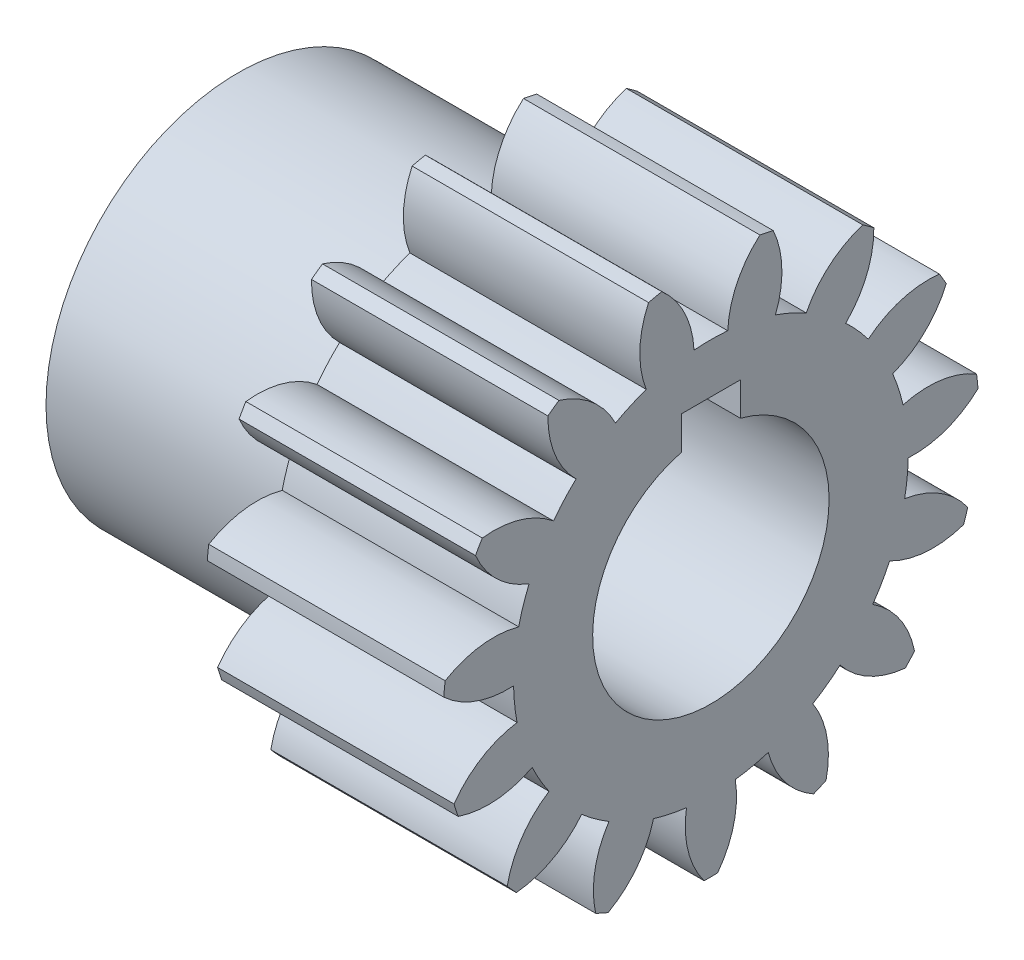
SolidWorks part; units mm, degrees
ref_plane "Plane1" through (0, 0, 0) normal (0, 0, 1) x (1, 0, 0)
ref_plane "Plane2" through (0, 0, 0) normal (0, 1, 0) x (1, 0, 0)
ref_plane "Plane3" through (0, 0, 0) normal (1, 0, 0) x (0, 0, -1)
sketch "HoldingSke" plane through (0, 0, 0) normal (0, 1, 0) x (1, 0, 0)
  line L0 (0, 0) -> (490.6903, -131.4801)
  line L1 (-15, 0) -> (100, 0) construction
  line L2 (0, 0) -> (-2.1039, 2.3779)
  line L3 (0, 0) -> (-11.863, 4.5341)
  line L4 (0, 0) -> (8.3417, 2.2352)
  line L5 (0, 0) -> (-17.849, -6.6571)
  line L6 (0, 0) -> (-7.8959, -5.3274)
  line L7 (-2.1039, 2.3779) -> (1.9966, 20.9814)
  line L8 (-76.2, 54.61) -> (-65.4837, 54.61)
  line L9 (-71.009, 38.7566) -> (-53.1078, 45.2721)
  line L10 (-76.2, 71.12) -> (104.1128, 71.12)
  line L11 (0, 0) -> (-9.525, 0)
  line L12 (-76.2, 101.6) -> (-76.1492, 101.6)
  line L13 (24.9733, 27.94) -> (52.9518, 28.4284)
  line L14 (24.9733, 27.94) -> (25.0241, 27.9398)
  line L15 (24.9733, 27.94) -> (100.4021, 29.52)
  circle A0 centre (0, 0) radius 4.7625
  circle A1 centre (0, 0) radius 7.7343
  circle A2 centre (0, 0) radius 7.7343
  circle A3 centre (0, 0) radius 4.7625
  dimension "MHD" = 15.4686
  dimension "Hub_dia" = 15.4686
  dimension "Bore" = 9.525
  dimension "MBD" = 9.525
  dimension "Num_teeth" = 15
  dimension "Pitch_radius" = 180.3128
  dimension "Pitch" = 508
  dimension "Width" = 9.525
  dimension "Overall_len" = 19.05
  dimension "Show_teeth" = 15
  dimension "Thickness" = 9.525
  dimension "OAL" = 19.0501
  dimension "T_dim" = 10.7163
  dimension "Ap" = 20
  dimension "H" = 19.05
  dimension "Backlash" = 0.0508
  dimension "Addendum_fac" = 1
  dimension "Dedendum_fac" = 1.2
  dimension "Clearance_fac" = 0.2
  dimension "Dedendum_add" = 0.0508
sketch "BasProSke" plane through (0, 0, 0) normal (0, 1, 0) x (1, 0, 0)
  line L0 (-10, 0) -> (60, 0) construction
  line L1 (0, 0) -> (0, 10.795)
  line L2 (0, 0) -> (9.525, 0)
  line L3 (9.525, 0) -> (9.525, 10.795)
  line L4 (9.525, 10.795) -> (0, 10.795)
  dimension "Diameter" = 21.59
  dimension "Thickness" = 9.525
revolve "Base-Revolve" add sketch "BasProSke" angle 360 about L0
sketch "TooCutSke" plane through (0, 0, 0) normal (1, 0, 0) x (0, 0, -1)
  line L1 (0, 0) -> (0, 107) construction
  line L2 (0, 0) -> (-1.0844, 9.4631) construction
  line L3 (0, 0) -> (-3.9427, 18.5491) construction
  line L4 (-1.0844, 9.4631) -> (-1.9714, 9.2745) construction
  arc A0 (0.6794, 7.9211) -> (-0.6794, 7.9211) centre (0, 0) ccw
  arc A1 (2.0006, 10.6338) -> (-2.0006, 10.6338) centre (0, 0) ccw
  circle A2 centre (0, 0) radius 9.525 construction
  circle A3 centre (0, 0) radius 8.9506 construction
  arc A4 (-0.6794, 7.9211) -> (-2.0006, 10.6338) centre (-4.4854, 7.7456) ccw
  arc A5 (2.0006, 10.6338) -> (0.6794, 7.9211) centre (4.4854, 7.7456) ccw
  dimension "Root_dia" = 15.9004
  dimension "Overcut_dia" = 21.6408
  dimension "Pitch_dia" = 19.05
  dimension "Base_dia" = 17.9011
  dimension "Flank_rad" = 3.81
  dimension "Half_ang" = 12
  dimension "Half_CT" = 0.9067
extrude "ToothCut" cut sketch "TooCutSke" along normal through all
fillet "Breaks" [suppressed] radius 0.0254
fillet "RootFillets" [suppressed] radius 0.3048
pattern_circular "TeethCuts" count 15 every 24 about axis through (-10, 0, 0) along (1, 0, 0) of "ToothCut", "RootFillets", "Breaks"
sketch "HubNeaOneSke" plane through (0, 0, 0) normal (-1, 0, 0) x (0, 0, 1)
  circle A0 centre (0, 0) radius 7.7343
  dimension "Diameter" = 15.4686
extrude "HubNearOne" add sketch "HubNeaOneSke" along normal blind 9.5251
sketch "HubNeaBotSke" plane through (0, 0, 0) normal (-1, 0, 0) x (0, 0, 1)
  circle A0 centre (0, 0) radius 7.7343
  dimension "Diameter" = 15.4686
extrude "HubNearBoth" [suppressed] add sketch "HubNeaBotSke" along normal blind 4.7625
ref_plane "FarPln" through (9.525, 0, 0) normal (1, 0, 0) x (0, 0, -1)
sketch "HubFarSke" plane through (9.525, 0, 0) normal (1, 0, 0) x (0, 0, -1)
  circle A0 centre (0, 0) radius 7.7343
  dimension "Diameter" = 15.4686
extrude "HubFar" [suppressed] add sketch "HubFarSke" along normal blind 4.7625
sketch "BorSke" plane through (0, 0, 0) normal (1, 0, 0) x (0, 0, -1)
  circle A0 centre (0, 0) radius 4.7625
  dimension "Diameter" = 9.525
extrude "Bore" cut sketch "BorSke" along normal mid plane 38.1001
sketch "KeySke" plane through (0, 0, 0) normal (1, 0, 0) x (0, 0, -1)
  line L0 (-1.1913, 0) -> (-1.1913, 5.9538)
  line L1 (-1.1913, 5.9538) -> (1.1913, 5.9538)
  line L2 (1.1913, 5.9538) -> (1.1913, 0)
  line L3 (0, 0) -> (0, 34) construction
  line L4 (-1.1913, 0) -> (1.1913, 0)
  dimension "Offset" = 5.9538
  dimension "Width" = 2.3825
extrude "Keyway" cut sketch "KeySke" along normal mid plane 38.1001
pattern_circular "Keyway2" [suppressed] count 2 every 90 about axis through (-10, 0, 0) along (1, 0, 0)
equation "' \"Pitch@HoldingSke\" = 4"
equation "' \"Num_teeth@HoldingSke\" = 12"
equation "' \"Ap@HoldingSke\" =  20"
equation "' \"Width@HoldingSke\" = 0.5"
equation "' \"Hub_dia@HoldingSke\"= 1"
equation "' \"Overall_len@HoldingSke\" = 1.0"
equation "' \"Bore@HoldingSke\" = 0.75"
equation "' \"T_dim@HoldingSke\" = 0.85"
equation "' \"Width@KeySke\" = 0.25"
equation "' \"Show_teeth@HoldingSke\" = 13"
equation "' \"Backlash@HoldingSke\" = 0.009"
equation "' \"Addendum_fac@HoldingSke\" = 1.0"
equation "' \"Dedendum_fac@HoldingSke\" = 1.25"
equation "' \"Dedendum_add@HoldingSke\" = 0.00005"
equation "' \"Clearance_fac@HoldingSke\" = 0.25"
equation "' \"Pitch@HoldingSke\" = 0.5"
equation "' \"Num_teeth@HoldingSke\" = 23"
equation "' \"Show_teeth@HoldingSke\" = 23"
equation "' \"Backlash@HoldingSke\" = 0.0375"
equation "\"Overcut_dia@TooCutSke\" = (\"Num_teeth@HoldingSke\" + 2 * \"Addendum_fac@HoldingSke\") / \"Pitch@HoldingSke\" + 0.002"
equation "\"Pitch_dia@TooCutSke\" = \"Num_teeth@HoldingSke\" / \"Pitch@HoldingSke\""
equation "\"Base_dia@TooCutSke\" = \"Num_teeth@HoldingSke\" / \"Pitch@HoldingSke\" * cos((\"Ap@HoldingSke\"  * 3.14159265 / 180))"
equation "\"Root_dia@TooCutSke\" = (\"Num_teeth@HoldingSke\" + 2) / \"Pitch@HoldingSke\" - 2 * (\"Addendum_fac@HoldingSke\" + \"Dedendum_fac@HoldingSke\") / \"Pitch@HoldingSke\" - \"Dedendum_add@HoldingSke\" * 2"
equation "\"Half_ang@TooCutSke\" = 180 / \"Num_teeth@HoldingSke\""
equation "\"Half_CT@TooCutSke\" = \"Num_teeth@HoldingSke\" / \"Pitch@HoldingSke\" * sin((3.14159265 / 2 / \"Num_teeth@HoldingSke\")) / 2 - 7 * \"Backlash@HoldingSke\" / 4"
equation "\"Flank_rad@TooCutSke\" = \"Num_teeth@HoldingSke\" / \"Pitch@HoldingSke\" / 5"
equation "\"Radius@RootFillets\" = \"Clearance_fac@HoldingSke\" / \"Pitch@HoldingSke\" + \"Dedendum_add@HoldingSke\""
equation "\"Break_rad@Breaks\" = 0.02 / \"Pitch@HoldingSke\""
equation "\"Thickness@HoldingSke\" = \"Width@HoldingSke\""
equation "\"OAL@HoldingSke\" = \"Thickness@HoldingSke\""
equation "\"MHD@HoldingSke\" = (\"Num_teeth@HoldingSke\" + 2) / \"Pitch@HoldingSke\" - 2 * (\"Addendum_fac@HoldingSke\" + \"Dedendum_fac@HoldingSke\")  / \"Pitch@HoldingSke\" - \"Dedendum_add@HoldingSke\" * 2"
equation "\"MBD@HoldingSke\" = (\"Num_teeth@HoldingSke\" + 2) / \"Pitch@HoldingSke\" - 2 * (\"Addendum_fac@HoldingSke\" + \"Dedendum_fac@HoldingSke\")  / \"Pitch@HoldingSke\" - \"Dedendum_add@HoldingSke\" * 2 - 0.002"
equation "\"MHD@HoldingSke\" = ((sgn( \"MHD@HoldingSke\" - \"Hub_dia@HoldingSke\" )-1)*( \"MHD@HoldingSke\" - \"Hub_dia@HoldingSke\" ))/-2+ \"Hub_dia@HoldingSke\""
equation "\"MBD@HoldingSke\" = ((sgn( \"MBD@HoldingSke\" - \"Bore@HoldingSke\" )-1)*( \"MBD@HoldingSke\" - \"Bore@HoldingSke\" ))/-2+ \"Bore@HoldingSke\""
equation "\"OAL@HoldingSke\" = ((sgn( \"OAL@HoldingSke\" - \"Overall_len@HoldingSke\" )+1)*( \"OAL@HoldingSke\" - \"Overall_len@HoldingSke\" ))/2 + \"Overall_len@HoldingSke\" + 0.000002"
equation "\"Num_teeth@TeethCuts\" = int( \"Show_teeth@HoldingSke\" ) + 1"
equation "\"Num_teeth@TeethCuts\" = ((sgn( \"Num_teeth@TeethCuts\" - \"Num_teeth@HoldingSke\" )-1)*( \"Num_teeth@TeethCuts\" - \"Num_teeth@HoldingSke\" ))/-2+ \"Num_teeth@HoldingSke\""
equation "\"Num_teeth@TeethCuts\" = ((sgn( \"Num_teeth@TeethCuts\" - 2.0)+1)*( \"Num_teeth@TeethCuts\" - 2.0))/2 +2.0"
equation "\"Angle@TeethCuts\" = 360.0 / \"Num_teeth@HoldingSke\""
equation "\"Diameter@BasProSke\" = (\"Num_teeth@HoldingSke\" + 2 * \"Addendum_fac@HoldingSke\") / \"Pitch@HoldingSke\""
equation "\"Thickness@BasProSke\"  = \"Thickness@HoldingSke\""
equation "' \"Fillet_rad@BasProSke\" =  \"Thickness@HoldingSke\" * 0.05"
equation "\"MHD@HoldingSke\" = ((sgn( \"MHD@HoldingSke\" - \"Root_dia@TooCutSke\" )-1)*( \"MHD@HoldingSke\" - \"Root_dia@TooCutSke\" ))/-2+ \"Root_dia@TooCutSke\""
equation "\"Diameter@HubNeaOneSke\" = \"MHD@HoldingSke\""
equation "\"Length@HubNearOne\" = \"OAL@HoldingSke\" - \"Thickness@BasProSke\""
equation "\"Diameter@HubNeaBotSke\" = \"MHD@HoldingSke\""
equation "\"Length@HubNearBoth\" = ( \"OAL@HoldingSke\" - \"Thickness@BasProSke\" ) / 2.0"
equation "\"Thickness@FarPln\" = \"Thickness@BasProSke\""
equation "\"Diameter@HubFarSke\" = \"MHD@HoldingSke\""
equation "\"Length@HubFar\" = ( \"OAL@HoldingSke\" - \"Thickness@BasProSke\" ) / 2.0"
equation "\"Diameter@BorSke\" = \"MBD@HoldingSke\""
equation "\"D1@Bore\" = \"OAL@HoldingSke\" * 2.0"
equation "\"D1@Keyway\" = \"OAL@HoldingSke\" * 2.0"
equation "\"Offset@KeySke\" = \"T_dim@HoldingSke\" - \"MBD@HoldingSke\" / 2.0"
